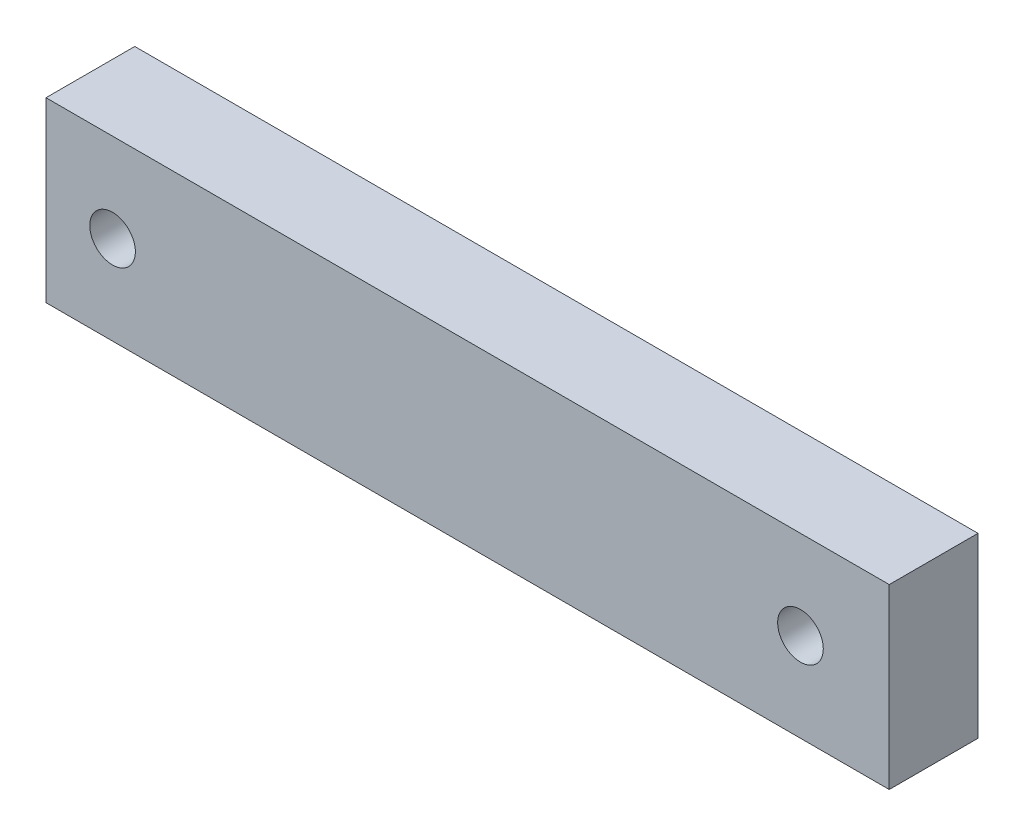
SolidWorks part; units mm, degrees
material "Acrylic (Medium-high impact)"
ref_plane "Front Plane" through (0, 0, 0) normal (0, 0, 1) x (1, 0, 0)
ref_plane "Top Plane" through (0, 0, 0) normal (0, 1, 0) x (1, 0, 0)
ref_plane "Right Plane" through (0, 0, 0) normal (1, 0, 0) x (0, 0, -1)
sketch "Sketch1" plane through (0, 0, 0) normal (0, 0, 1) x (1, 0, 0)
  line L1 (-30.1625, -6.35) -> (30.1625, -6.35)
  line L2 (-30.1625, -6.35) -> (-30.1625, 6.35)
  line L3 (-30.1625, 6.35) -> (30.1625, 6.35)
  line L4 (30.1625, -6.35) -> (30.1625, 6.35)
  line L5 (-30.1625, -6.35) -> (30.1625, 6.35) construction
  line L6 (-30.1625, 6.35) -> (30.1625, -6.35) construction
  point P0 (0, 0)
  dimension "D1" = 60.325
  dimension "D2" = 12.7
extrude "Boss-Extrude1" add sketch "Sketch1" along normal blind 6.35
sketch "Sketch2" plane through (0, 0, 6.35) normal (0, 0, 1) x (1, 0, 0)
  line L0 (-30.1625, 0) -> (-25.4, 0) construction
  line L1 (-30.1625, 6.35) -> (-30.1625, -6.35) construction
  line L2 (-25.4, 0) -> (23.8125, 0) construction
  line L3 (30.1625, -6.35) -> (30.1625, 6.35) construction
  line L4 (23.8125, 0) -> (30.1625, 0) construction
  dimension "D1" = 49.2125
  dimension "D2" = 4.7625
hole_wizard "#4 Clearance Hole1" positions "Sketch4" profile "Sketch3" hole size "#4" standard "Ansi Inch"
sketch "Sketch4" plane through (0, 0, 6.35) normal (0, 0, 1) x (1, 0, 0)
  point P1 (-25.4, 0)
  point P4 (23.8125, 0)
sketch "Sketch3" plane through (-25.4, 0, 6.35) normal (1, 0, 0) x (0, -1, 0)
  line L0 (0, 0) -> (0, 13.6806)
  line L1 (0, 13.6806) -> (1.6319, 12.7)
  line L2 (1.6319, 12.7) -> (1.6319, 0)
  line L5 (1.6319, 0) -> (0, 0)
  line L10 (0, 13.6806) -> (-1.6319, 12.7) construction
  line L11 (0, -6.35) -> (0, 107.95) construction
  dimension "Hole Dia." = 3.2639
  dimension "Hole Depth" = 12.7
  dimension "Drill Angle" = 118
